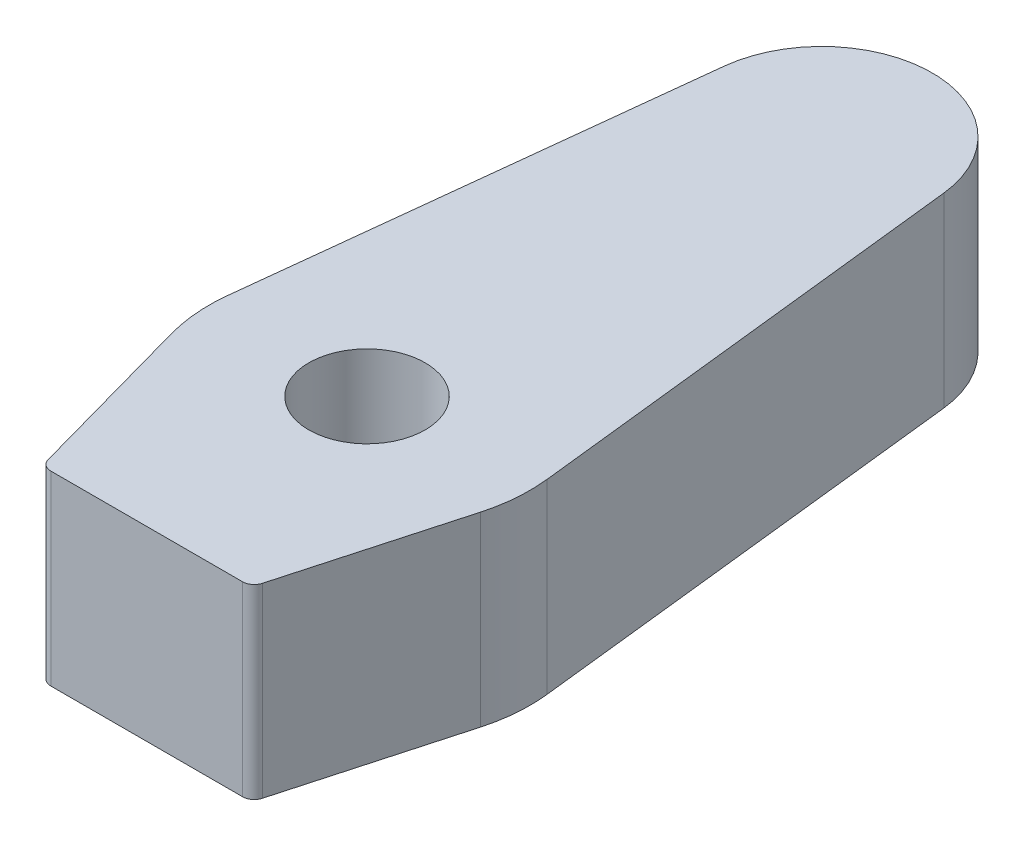
SolidWorks part; units mm, degrees
ref_plane "Front Plane" through (0, 0, 0) normal (0, 0, 1) x (1, 0, 0)
ref_plane "Top Plane" through (0, 0, 0) normal (0, 1, 0) x (1, 0, 0)
ref_plane "Right Plane" through (0, 0, 0) normal (1, 0, 0) x (0, 0, -1)
sketch "Sketch1" plane through (0, 0, 0) normal (0, 1, 0) x (1, 0, 0)
  line L3 (-4.12, -14.5) -> (4.12, -14.5)
  line L4 (-4.6017, -14.1338) -> (-6.6382, -6.8025)
  line L5 (-4.721, 15.0242) -> (-6.8508, -4.1564)
  line L6 (4.721, 15.0242) -> (6.8508, -4.1564)
  line L7 (4.6017, -14.1338) -> (6.6382, -6.8025)
  arc A0 (4.721, 15.0242) -> (-4.721, 15.0242) centre (0, 14.5) ccw
  circle A1 centre (0, -5.5) radius 1.6
  arc A2 (4.12, -14.5) -> (4.6017, -14.1338) centre (4.12, -14) ccw
  arc A3 (-4.12, -14.5) -> (-4.6017, -14.1338) centre (-4.12, -14) cw
  arc A4 (6.6382, -6.8025) -> (6.8508, -4.1564) centre (-0.1064, -4.929) ccw
  arc A5 (-6.8508, -4.1564) -> (-6.6382, -6.8025) centre (0.1064, -4.929) ccw
  point P4 (0, 0)
  point P6 (0, 0)
  point P11 (0, -14.5)
  point P13 (0, -5.5)
  dimension "D2" = 9.5
  dimension "D1" = 3.2
  dimension "D3" = 0.5
  dimension "D4" = 0.5
  dimension "D5" = 7
extrude "Boss-Extrude4" add sketch "Sketch1" along normal blind 8 contours L6 A4 L7 A2 L3 A3 L4 A5 L5 A0
sketch "Sketch2" plane through (0, 8, 0) normal (0, 1, 0) x (1, 0, 0)
  circle A0 centre (-0.1064, -4.929) radius 2.5
  dimension "D1" = 5
extrude "Cut-Extrude1" cut sketch "Sketch2" against normal blind 5.15
